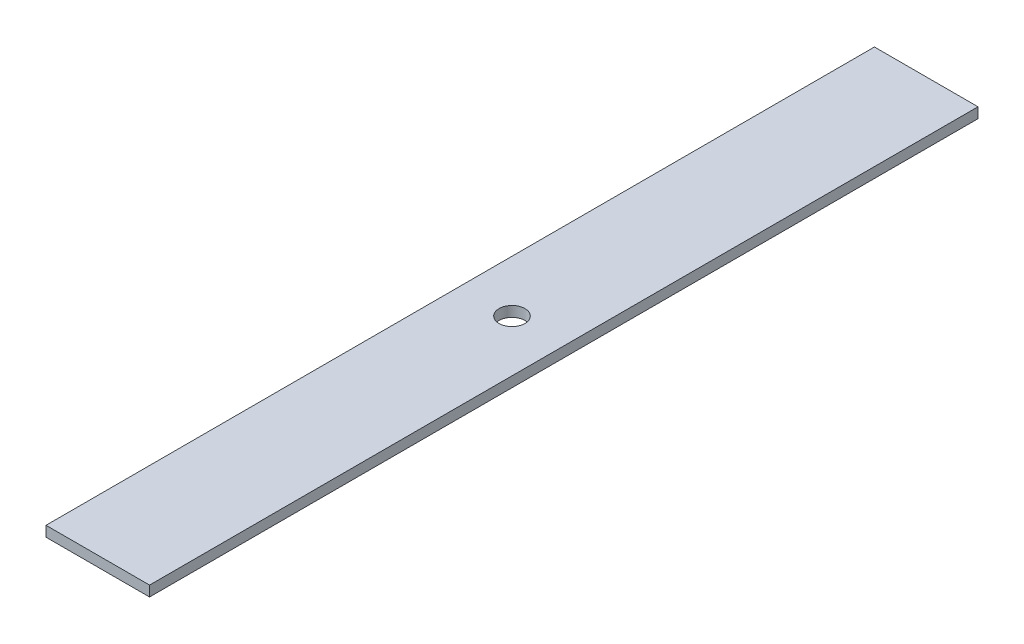
SolidWorks part; units mm, degrees
ref_plane "Front Plane" through (0, 0, 0) normal (0, 0, 1) x (1, 0, 0)
ref_plane "Top Plane" through (0, 0, 0) normal (0, 1, 0) x (1, 0, 0)
ref_plane "Right Plane" through (0, 0, 0) normal (1, 0, 0) x (0, 0, -1)
sketch "sketch" plane through (0, 0, 0) normal (0, 1, 0) x (1, 0, 0)
  line L1 (0, 0) -> (25.4, 0)
  line L2 (0, 0) -> (0, 203.2)
  line L3 (0, 203.2) -> (25.4, 203.2)
  line L4 (25.4, 0) -> (25.4, 203.2)
  circle A0 centre (12.7, 101.6) radius 3.175
  dimension "D3" = 6.35
  dimension "D1" = 25.4
  dimension "D2" = 203.2
  dimension "D4" = 12.7
  dimension "D5" = 101.6
extrude "Boss-Extrude2" add sketch "sketch" along normal blind 2.54
ref_plane "Plane1" through (69.1498, 0, -119.7709) normal (-0.5, 0, 0.866) x (0.866, 0, 0.5)
